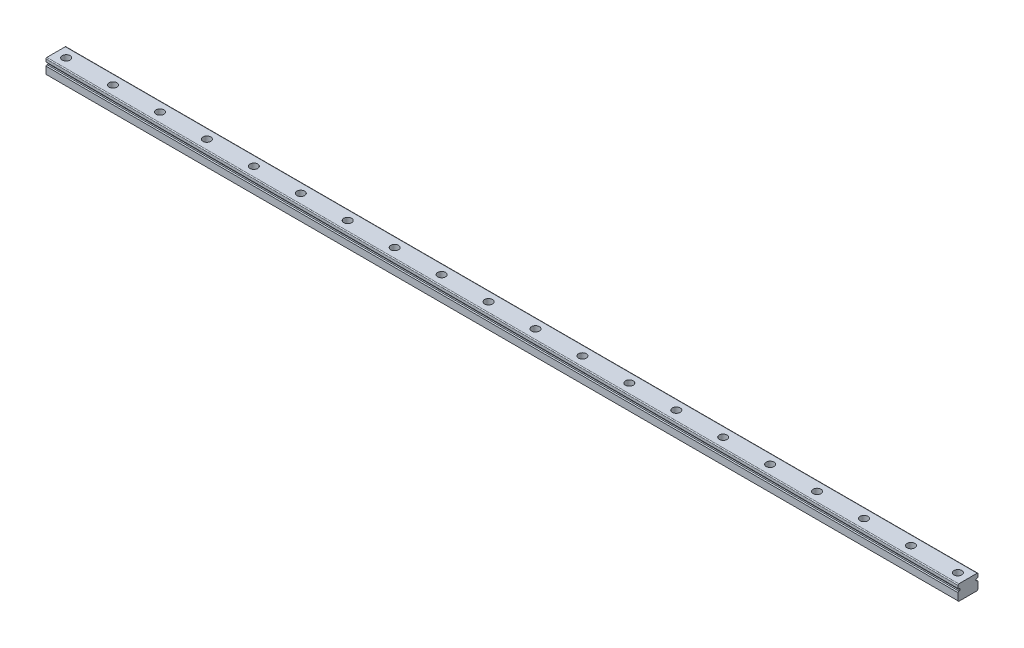
SolidWorks part; units mm, degrees
ref_plane "前视基准面" through (0, 0, 0) normal (0, 0, 1) x (1, 0, 0)
ref_plane "上视基准面" through (0, 0, 0) normal (0, 1, 0) x (1, 0, 0)
ref_plane "右视基准面" through (0, 0, 0) normal (1, 0, 0) x (0, 0, -1)
sketch "草图1" plane through (0, 0, 0) normal (1, 0, 0) x (0, 0, -1)
  line L0 (0, 45.8513) -> (0, -28.9063) construction
  line L1 (-20.5, 0) -> (20.5, 0)
  line L2 (22.5, 2) -> (22.5, 18)
  line L3 (20.5, 20) -> (17.5, 20)
  line L4 (17.5, 20) -> (17.5, 24)
  line L5 (17.5, 24) -> (20.5, 24)
  line L6 (22.5, 26) -> (22.5, 32)
  line L7 (20.5, 34) -> (-20.5, 34)
  line L8 (22.5, 18) -> (20.5, 20)
  line L9 (20.5, 24) -> (22.5, 26)
  line L10 (20.5, 0) -> (22.5, 2)
  line L11 (-20.5, 0) -> (-22.5, 2)
  line L12 (-20.5, 24) -> (-22.5, 26)
  line L13 (-22.5, 18) -> (-20.5, 20)
  line L14 (-22.5, 26) -> (-22.5, 32)
  line L15 (-17.5, 24) -> (-20.5, 24)
  line L16 (-17.5, 20) -> (-17.5, 24)
  line L17 (-20.5, 20) -> (-17.5, 20)
  line L18 (-22.5, 2) -> (-22.5, 18)
  arc A0 (22.5, 32) -> (20.5, 34) centre (20.5, 32) ccw
  arc A1 (-22.5, 32) -> (-20.5, 34) centre (-20.5, 32) cw
  point P3 (-22.5, 24)
  point P4 (22.5, 0)
  point P6 (22.5, 20)
  point P9 (22.5, 24)
  point P28 (0, 34)
  point P30 (0, 0)
  point P31 (-22.5, 20)
  point P32 (-22.5, 0)
  dimension "D7" = 2
  dimension "D1" = 22.5
  dimension "D2" = 34
  dimension "D3" = 4
  dimension "D4" = 14
  dimension "D5" = 5
  dimension "D6" = 22.5
extrude "凸台-拉伸1" add sketch "草图1" along normal blind 2040
sketch "草图2" plane through (0, 34, 0) normal (0, 1, 0) x (1, 0, 0)
  line L0 (22.5, 86.776) -> (22.5, -86.776) construction
  line L1 (-27.8412, 0) -> (95.3925, 0) construction
  circle A0 centre (22.5, 0) radius 8.75
  dimension "D2" = 17.5
  dimension "D1" = 22.5
extrude "切除-拉伸1" cut sketch "草图2" against normal blind 14
sketch "草图3" plane through (0, 0, 0) normal (0, -1, 0) x (1, 0, 0)
  line L0 (22.5, 90.0124) -> (22.5, -113.9744) construction
  line L1 (-65.7277, 0) -> (126.0199, 0) construction
  circle A0 centre (22.5, 0) radius 5.5
  dimension "D2" = 11
  dimension "D1" = 22.5
extrude "切除-拉伸2" cut sketch "草图3" against normal up to next
pattern_linear "阵列(线性)1" count 20 spacing 105 along (1, 0, 0) of "切除-拉伸2", "切除-拉伸1"
